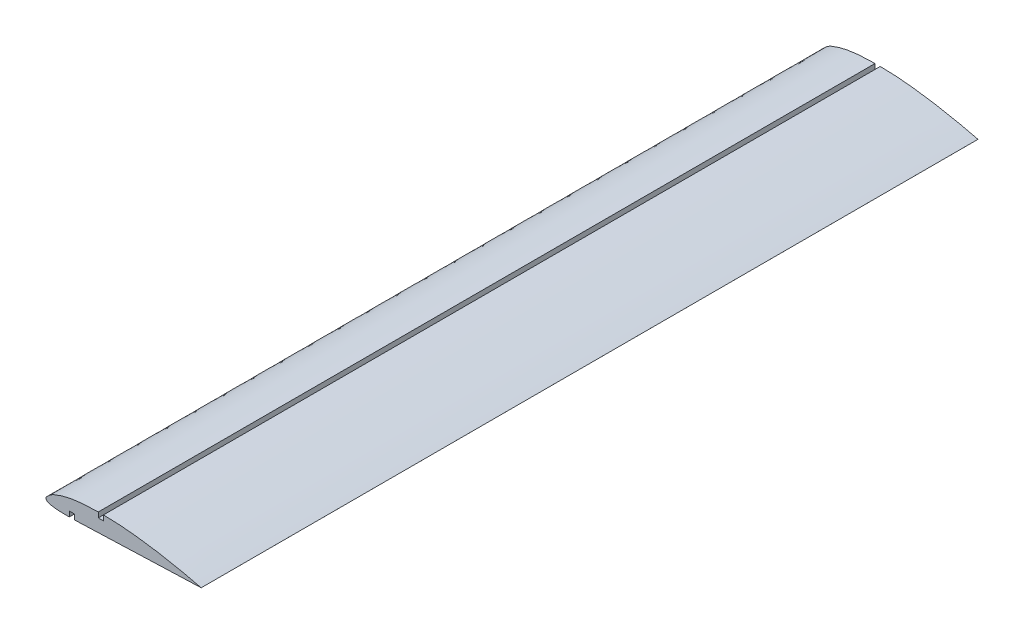
SolidWorks part; units mm, degrees
ref_plane "Ön Düzlem" through (0, 0, 0) normal (0, 0, 1) x (1, 0, 0)
ref_plane "Üst Düzlem" through (0, 0, 0) normal (0, 1, 0) x (1, 0, 0)
ref_plane "Sağ Düzlem" through (0, 0, 0) normal (1, 0, 0) x (0, 0, -1)
sketch "Sketch1" plane through (0, 0, 0) normal (0, 0, 1) x (1, 0, 0)
  line L0 (273.8644, 129.7584) -> (1369.8644, 129.7584) construction
  line L1 (149.8581, 0) -> (149.8558, -0.0087)
  spline S0 degree 3 poles (149.8581, 0) (148.0649, 0.471) (143.2248, 1.7424) (133.1757, 3.886) (119.4995, 6.7583) (102.5414, 9.7444) (85.9645, 11.9563) (70.8168, 13.3138) (56.6678, 13.8481) (41.7647, 13.6427) (27.8783, 12.5388) (17.5169, 10.3502) (10.936, 8.1212) (5.6282, 6.0173) (2.2408, 3.1599) (-0.2937, 0.7197) (0.5423, -2.4008) (4.9566, -3.5377) (10.6122, -4.3278) (18.7708, -4.4982) (30.5005, -4.4934) (45.7845, -3.9122) (66.3708, -3.1228) (87.0163, -2.3781) (108.488, -1.5762) (124.5472, -1.0028) (137.7849, -0.5219) (145.1223, -0.2664) (148.9169, -0.06) (149.8558, -0.0087) knots 0 0 0 0 0.018163 0.049023 0.100644 0.15508 0.217678 0.264436 0.304025 0.356345 0.410393 0.440307 0.459596 0.478843 0.494821 0.504999 0.508601 0.524256 0.542616 0.567477 0.602874 0.658123 0.717036 0.804816 0.860487 0.927555 0.96225 0.990269 0.999481 0.999481 0.999481 0.999481
extrude "Boss-Extrude1" add sketch "Sketch1" along normal blind 750
sketch "Sketch2" plane through (0, 0, 0) normal (0, 0, -1) x (-1, 0, 0)
  line L0 (-22.5043, -4.4841) -> (-22.5043, 0.5453)
  line L1 (-22.5043, 0.5453) -> (-27.5043, 0.5453)
  line L2 (-27.5043, 0.5453) -> (-27.5043, -4.4547)
  line L3 (-50.4738, 13.7215) -> (-50.4738, 8.7215)
  line L4 (-50.4738, 8.7215) -> (-55.4738, 8.7215)
  line L5 (-55.4738, 8.7215) -> (-55.4738, 13.7367)
  line L6 (-50.4738, 13.7215) -> (-50.4738, 14.8698)
  line L7 (-50.4738, 14.8698) -> (-55.4738, 14.8698)
  line L8 (-55.4738, 14.8698) -> (-55.4738, 13.7367)
  line L9 (-22.5043, -4.4841) -> (-22.5043, -6.8537)
  line L10 (-22.5043, -6.8537) -> (-27.5043, -6.8537)
  line L11 (-27.5043, -6.8537) -> (-27.5043, -4.4547)
  spline S1 degree 3 poles (-149.8581, 0) (-148.0649, 0.471) (-143.2248, 1.7424) (-133.1757, 3.886) (-119.4995, 6.7583) (-102.5414, 9.7444) (-85.9645, 11.9563) (-70.8168, 13.3138) (-56.6678, 13.8481) (-41.7647, 13.6427) (-27.8783, 12.5388) (-17.5169, 10.3502) (-10.936, 8.1212) (-5.6282, 6.0173) (-2.2408, 3.1599) (0.2937, 0.7197) (-0.5423, -2.4008) (-4.9566, -3.5377) (-10.6122, -4.3278) (-18.7708, -4.4982) (-30.5005, -4.4934) (-45.7845, -3.9122) (-66.3708, -3.1228) (-87.0163, -2.3781) (-108.488, -1.5762) (-124.5472, -1.0028) (-137.7849, -0.5219) (-145.1223, -0.2664) (-148.9169, -0.06) (-149.8558, -0.0087) knots 0 0 0 0 0.018163 0.049023 0.100644 0.15508 0.217678 0.264436 0.304025 0.356345 0.410393 0.440307 0.459596 0.478843 0.494821 0.504999 0.508601 0.524256 0.542616 0.567477 0.602874 0.658123 0.717036 0.804816 0.860487 0.927555 0.96225 0.990269 0.999481 0.999481 0.999481 0.999481 construction
  dimension "D1" = 5
  dimension "D2" = 5
  dimension "D3" = 5
  dimension "D4" = 5
extrude "Cut-Extrude1" cut sketch "Sketch2" against normal blind 792
sketch "Sketch3" plane through (0, 0, 0) normal (0, 0, 1) x (1, 0, 0)
  line L0 (0, 0) -> (149.6035, 0) construction
